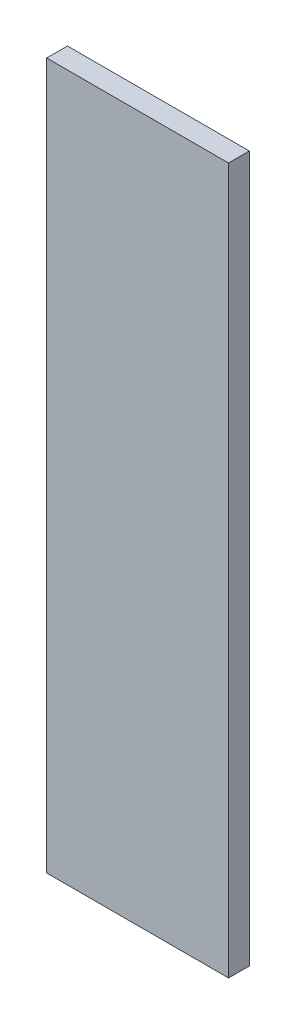
SolidWorks part; units mm, degrees
ref_plane "Front Plane" through (0, 0, 0) normal (0, 0, 1) x (1, 0, 0)
ref_plane "Top Plane" through (0, 0, 0) normal (0, 1, 0) x (1, 0, 0)
ref_plane "Right Plane" through (0, 0, 0) normal (1, 0, 0) x (0, 0, -1)
sketch "Sketch1" plane through (0, 0, 0) normal (0, 0, 1) x (1, 0, 0)
  line L1 (-16.0087, 29.2306) -> (150.6788, 29.2306)
  line L2 (-16.0087, 29.2306) -> (-16.0087, -617.7074)
  line L3 (-16.0087, -617.7074) -> (150.6788, -617.7074)
  line L4 (150.6788, 29.2306) -> (150.6788, -617.7074)
  line L5 (-16.0087, 29.2306) -> (150.6788, -617.7074) construction
  line L6 (-16.0087, -617.7074) -> (150.6788, 29.2306) construction
  point P0 (67.3351, -294.2384)
  dimension "D1" = 646.938
  dimension "D2" = 166.6875
extrude "Boss-Extrude1" add sketch "Sketch1" along normal blind 19.05 contours L2 L1 L4 L3
